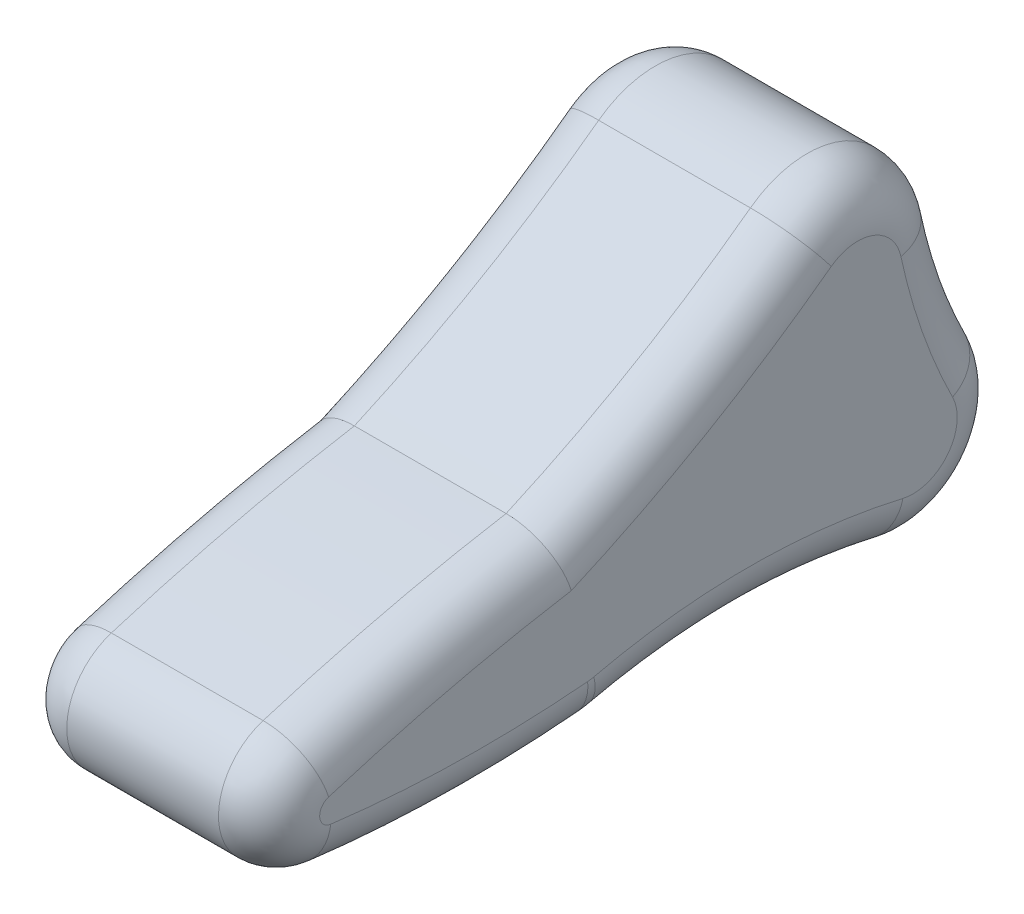
SolidWorks part; units mm, degrees
material "PW90:Mi:0:30:C1:0:1:2:Re:16:"
ref_plane "XY" through (0, 0, 0) normal (0, 0, 1) x (1, 0, 0)
ref_plane "YZ" through (0, 0, 0) normal (0, 1, 0) x (1, 0, 0)
ref_plane "XZ" through (0, 0, 0) normal (1, 0, 0) x (0, 0, -1)
ref_plane "Leg-plane" through (114.3, 0, 0) normal (1, 0, 0) x (0, 0, -1)
sketch "Sketch11" plane through (114.3, 0, 0) normal (1, 0, 0) x (0, 0, -1)
  line L0 (48.1295, -1222.515) -> (25.9157, -1159.015) construction
  line L1 (48.1295, -1222.515) -> (-84.0695, -1222.515) construction
  line L2 (-84.0695, -1222.515) -> (25.9157, -1159.015) construction
  line L3 (0, 432.2232) -> (0, -432.2232) construction
  line L4 (-246.7387, -1260.615) -> (307.6517, -1260.615) construction
  arc A0 (63.1782, -1151.0705) -> (3.1582, -1128.4584) centre (25.9157, -1159.015) ccw
  arc A1 (39.5078, -1259.6267) -> (82.2186, -1205.4991) centre (48.1295, -1222.515) ccw
  arc A2 (-99.1536, -1187.5282) -> (-75.4478, -1259.6267) centre (-84.0695, -1222.515) ccw
  arc A3 (82.2186, -1205.4991) -> (63.1782, -1151.0705) centre (286.7533, -1103.4035) cw
  arc A4 (39.5078, -1259.6267) -> (-75.4478, -1259.6267) centre (-17.97, -1507.0379) ccw
  arc A5 (-99.1536, -1187.5282) -> (3.1582, -1128.4584) centre (-300.2747, -721.0367) ccw
  dimension "D1" = 38.1
  dimension "D2" = 38.1
  dimension "D3" = 254
  dimension "D4" = 508
  dimension "D5" = 101.6
  dimension "D6" = 228.6
  dimension "D7" = 19.281
  dimension "D8" = 127
extrude "Base-Extrude" add sketch "Sketch11" along normal mid plane 101.6
sketch "Sketch12" plane through (114.3, 0, 0) normal (1, 0, 0) x (0, 0, -1)
  line L0 (-185.1062, -1233.199) -> (-84.0695, -1222.515) construction
  line L1 (0, 432.2232) -> (0, -432.2232) construction
  arc A0 (-80.7677, -1260.4717) -> (-90.1885, -1184.9096) centre (-84.0695, -1222.515) ccw
  arc A1 (-192.5992, -1208.9294) -> (-188.2807, -1258.3999) centre (-185.1062, -1233.199) ccw
  arc A2 (-192.5992, -1208.9294) -> (-90.1885, -1184.9096) centre (32.1918, -1937.018) cw
  arc A3 (-188.2807, -1258.3999) -> (-80.7677, -1260.4717) centre (-124.7917, -754.3829) ccw
  dimension "D2" = 762
  dimension "D3" = 25.4
  dimension "D4" = 38.1
  dimension "D5" = 508
  dimension "D1" = 96.036
  dimension "D6" = 101.6
extrude "Boss-Extrude1" add sketch "Sketch12" along normal mid plane 101.6
fillet "Fillet1" radius 20.32
